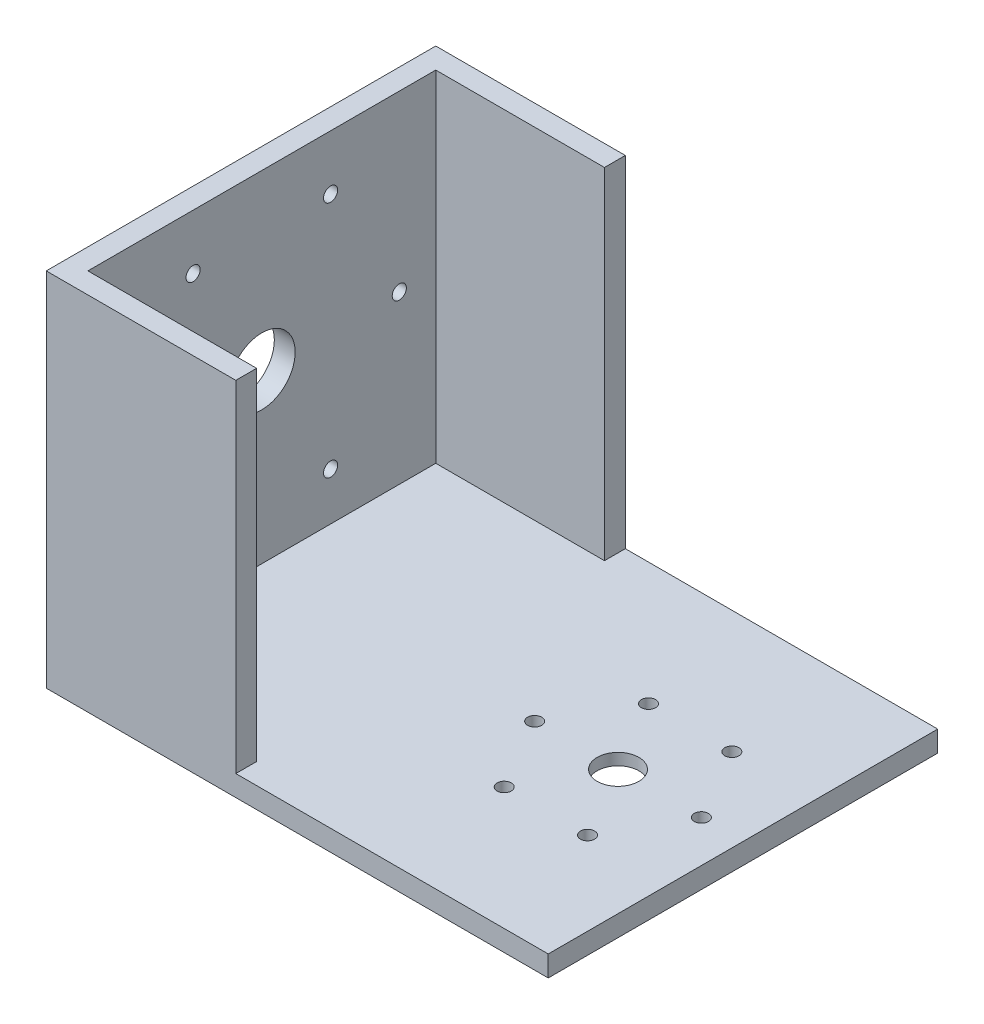
SolidWorks part; units mm, degrees
ref_plane "Front Plane" through (0, 0, 0) normal (0, 0, 1) x (1, 0, 0)
ref_plane "Top Plane" through (0, 0, 0) normal (0, 1, 0) x (1, 0, 0)
ref_plane "Right Plane" through (0, 0, 0) normal (1, 0, 0) x (0, 0, -1)
sketch "SK_Output_Plate" plane through (0, 0, 0) normal (0, 1, 0) x (1, 0, 0)
  line L0 (-90.5, 46.75) -> (30, 46.75)
  line L1 (30, 46.75) -> (30, -46.75)
  line L2 (30, -46.75) -> (-90.5, -46.75)
  line L3 (-90.5, -46.75) -> (-90.5, 46.75)
  circle A0 centre (20, 0) radius 1.7
  circle A1 centre (10, 17.3205) radius 1.7
  circle A2 centre (-10, 17.3205) radius 1.7
  circle A3 centre (-20, 0) radius 1.7
  circle A4 centre (-10, -17.3205) radius 1.7
  circle A5 centre (10, -17.3205) radius 1.7
  circle A6 centre (0, 0) radius 5
  dimension "D9_SK_Output_Plate" = 3.4
  dimension "D11_SK_Output_Plate" = 3.4
  dimension "D14_SK_Output_Plate" = 3.4
  dimension "D17_SK_Output_Plate" = 3.4
  dimension "D19_SK_Output_Plate" = 3.4
  dimension "D22_SK_Output_Plate" = 3.4
  dimension "D25_SK_Output_Plate" = 10
  dimension "P1" = 90.5
  dimension "P2" = 46.75
  dimension "P3" = 30
  dimension "P4" = 46.75
  dimension "P5" = 30
  dimension "P6" = 46.75
  dimension "P7" = 90.5
  dimension "P8" = 46.75
  dimension "P10" = 20
  dimension "P12" = 10
  dimension "P13" = 17.3205
  dimension "P15" = 10
  dimension "P16" = 17.3205
  dimension "P18" = 20
  dimension "P20" = 10
  dimension "P21" = 17.3205
  dimension "P23" = 10
  dimension "P24" = 17.3205
extrude "Output_Plate" add sketch "SK_Output_Plate" along normal blind 5
sketch "SK_Pitch_Pilot_Recess" plane through (0, 0, 0) normal (0, 1, 0) x (1, 0, 0)
  circle A0 centre (0, 0) radius 15.15
  dimension "D1_SK_Pitch_Pilot_Recess" = 30.3
extrude "Pitch_Pilot_Recess" cut sketch "SK_Pitch_Pilot_Recess" along normal blind 2.2
ref_plane "PL_Rear_Plate_base" through (-90.5, 0, 0) normal (1, 0, 0) x (0, 0, -1)
sketch "SK_Rear_Plate" plane through (-90.5, 0, 0) normal (1, 0, 0) x (0, 0, -1)
  line L0 (46.75, 0) -> (46.75, 86.75)
  line L1 (46.75, 86.75) -> (-46.75, 86.75)
  line L2 (-46.75, 86.75) -> (-46.75, 0)
  line L3 (-46.75, 0) -> (46.75, 0)
  circle A0 centre (0, 45) radius 8
  circle A1 centre (33, 45) radius 1.7
  circle A2 centre (16.5, 73.5788) radius 1.7
  circle A3 centre (-16.5, 73.5788) radius 1.7
  circle A4 centre (-33, 45) radius 1.7
  circle A5 centre (-16.5, 16.4212) radius 1.7
  circle A6 centre (16.5, 16.4212) radius 1.7
  dimension "D7_SK_Rear_Plate" = 16
  dimension "D9_SK_Rear_Plate" = 3.4
  dimension "D12_SK_Rear_Plate" = 3.4
  dimension "D15_SK_Rear_Plate" = 3.4
  dimension "D18_SK_Rear_Plate" = 3.4
  dimension "D21_SK_Rear_Plate" = 3.4
  dimension "D24_SK_Rear_Plate" = 3.4
  dimension "P1" = 46.75
  dimension "P2" = 46.75
  dimension "P3" = 86.75
  dimension "P4" = 46.75
  dimension "P5" = 86.75
  dimension "P6" = 46.75
  dimension "P8" = 45
  dimension "P10" = 33
  dimension "P11" = 45
  dimension "P13" = 16.5
  dimension "P14" = 73.5788
  dimension "P16" = 16.5
  dimension "P17" = 73.5788
  dimension "P19" = 33
  dimension "P20" = 45
  dimension "P22" = 16.5
  dimension "P23" = 16.4212
  dimension "P25" = 16.5
  dimension "P26" = 16.4212
extrude "Rear_Plate" add sketch "SK_Rear_Plate" along normal blind 5
ref_plane "PL_Top_Plate_base" through (0, 0, 41.75) normal (0, 0, 1) x (1, 0, 0)
sketch "SK_Top_Plate" plane through (0, 0, 41.75) normal (0, 0, 1) x (1, 0, 0)
  line L0 (-90.5, 0) -> (-45, 0)
  line L1 (-45, 0) -> (-45, 86.75)
  line L2 (-45, 86.75) -> (-90.5, 86.75)
  line L3 (-90.5, 86.75) -> (-90.5, 0)
  dimension "P1" = 90.5
  dimension "P2" = 45
  dimension "P3" = 45
  dimension "P4" = 86.75
  dimension "P5" = 90.5
  dimension "P6" = 86.75
extrude "Top_Plate" add sketch "SK_Top_Plate" along normal blind 5
ref_plane "PL_Bottom_Plate_base" through (0, 0, -46.75) normal (0, 0, 1) x (1, 0, 0)
sketch "SK_Bottom_Plate" plane through (0, 0, -46.75) normal (0, 0, 1) x (1, 0, 0)
  line L0 (-90.5, 0) -> (-45, 0)
  line L1 (-45, 0) -> (-45, 86.75)
  line L2 (-45, 86.75) -> (-90.5, 86.75)
  line L3 (-90.5, 86.75) -> (-90.5, 0)
  dimension "P1" = 90.5
  dimension "P2" = 45
  dimension "P3" = 45
  dimension "P4" = 86.75
  dimension "P5" = 90.5
  dimension "P6" = 86.75
extrude "Bottom_Plate" add sketch "SK_Bottom_Plate" along normal blind 5
equation "\"Roll_axis_y\" = 45"
equation "\"Roll_rear_x\" = -85.5"
